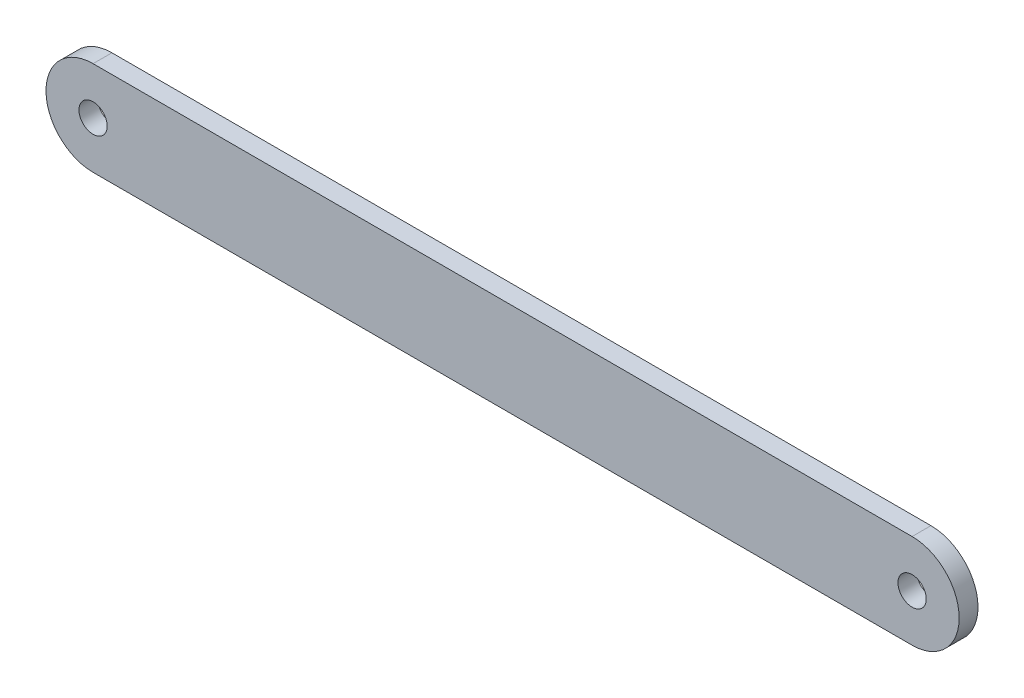
SolidWorks part; units mm, degrees
material "3.3535 (EN-AW 5754)"
ref_plane "Front" through (0, 0, 0) normal (0, 0, 1) x (1, 0, 0)
ref_plane "Top" through (0, 0, 0) normal (0, 1, 0) x (1, 0, 0)
ref_plane "Right" through (0, 0, 0) normal (1, 0, 0) x (0, 0, -1)
sketch "Esquisse1" plane through (0, 0, 0) normal (0, 0, 1) x (1, 0, 0)
  line L0 (-43.5, 0) -> (43.5, 0) construction
  line L1 (-43.5, 5) -> (43.5, 5)
  line L2 (-43.5, -5) -> (43.5, -5)
  arc A0 (-43.5, 5) -> (-43.5, -5) centre (-43.5, 0) ccw
  arc A1 (43.5, -5) -> (43.5, 5) centre (43.5, 0) ccw
  circle A2 centre (-43.5, 0) radius 1.5
  circle A3 centre (43.5, 0) radius 1.5
  point P2 (0, 0)
  dimension "D1" = 3
  dimension "D2" = 10
  dimension "D3" = 87
extrude "Boss.-Extru.1" add sketch "Esquisse1" along normal blind 2
